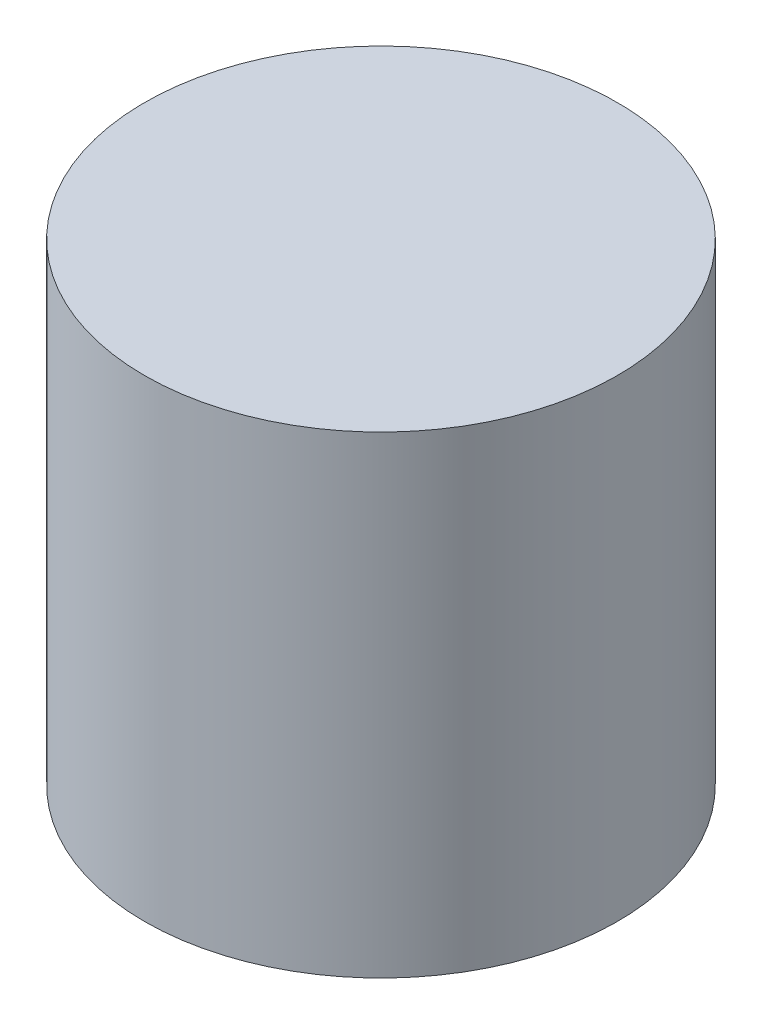
SolidWorks part; units mm, degrees
ref_plane "Front Plane" through (0, 0, 0) normal (0, 0, 1) x (1, 0, 0)
ref_plane "Top Plane" through (0, 0, 0) normal (0, 1, 0) x (1, 0, 0)
ref_plane "Right Plane" through (0, 0, 0) normal (1, 0, 0) x (0, 0, -1)
sketch "Sketch1" plane through (0, 0, 0) normal (0, 1, 0) x (1, 0, 0)
  circle A0 centre (0, 0) radius 8.5
  dimension "D1" = 17
extrude "Boss-Extrude1" add sketch "Sketch1" along normal blind 17
sketch "Sketch2" plane through (0, 0, 0) normal (0, -1, 0) x (1, 0, 0)
  circle A0 centre (0, 0) radius 3
  dimension "D1" = 6
extrude "Cut-Extrude1" cut sketch "Sketch2" against normal blind 10
